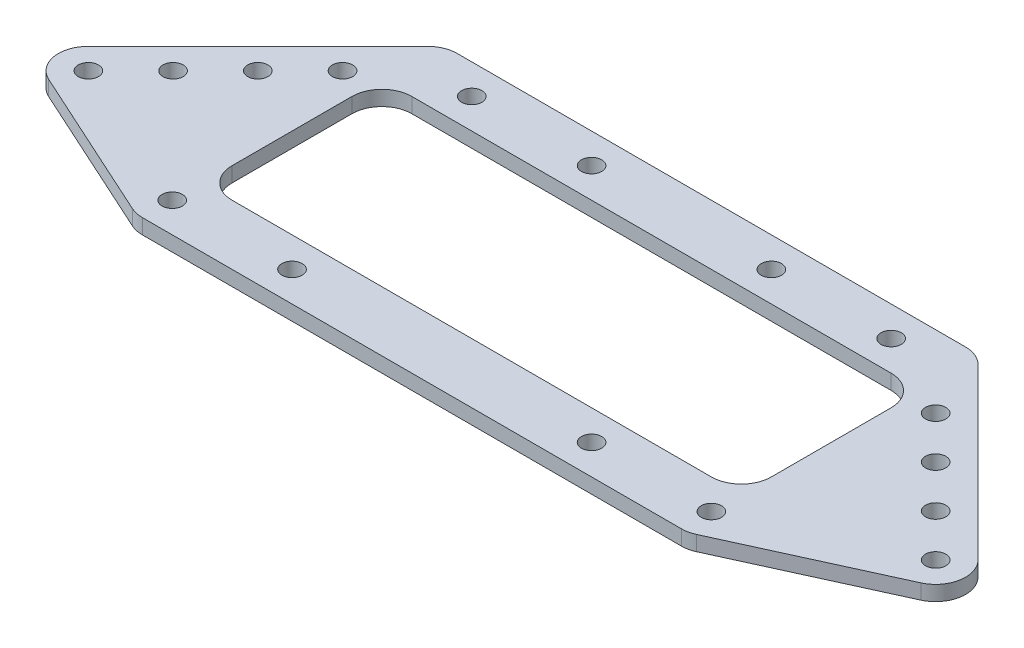
SolidWorks part; units mm, degrees
ref_plane "Front Plane" through (0, 0, 0) normal (0, 0, 1) x (1, 0, 0)
ref_plane "Top Plane" through (0, 0, 0) normal (0, 1, 0) x (1, 0, 0)
ref_plane "Right Plane" through (0, 0, 0) normal (1, 0, 0) x (0, 0, -1)
sketch "Sketch1" plane through (0, 0, 0) normal (0, 1, 0) x (1, 0, 0)
  line L0 (44.45, 0) -> (44.45, -7.0248) construction
  line L1 (98.3315, 6.35) -> (-9.4315, 6.35)
  line L2 (95.25, -6.35) -> (-6.35, -6.35)
  line L3 (-12.7, -12.7) -> (-12.7, -38.1)
  line L4 (-6.35, -44.45) -> (95.25, -44.45)
  line L5 (0, 0) -> (-37.4363, 0) construction
  line L6 (-9.4315, 0) -> (-60.1279, -50.6964) construction
  line L7 (-49.8427, -31.4309) -> (-13.9217, 4.4901)
  line L8 (-47.9856, -41.6994) -> (-15.3331, -56.5784)
  line L9 (-12.7, -57.15) -> (101.6, -57.15)
  line L10 (101.6, -12.7) -> (101.6, -38.1)
  line L11 (136.8856, -41.6994) -> (104.2331, -56.5784)
  line L12 (138.7427, -31.4309) -> (102.8217, 4.4901)
  line L13 (110.5803, -12.2487) -> (44.45, 53.8815) construction
  circle A0 centre (0, 0) radius 2.15
  circle A1 centre (25.4, 0) radius 2.15
  circle A2 centre (-18.4118, -8.9803) radius 2.15
  circle A3 centre (-27.392, -17.9605) radius 2.15
  circle A4 centre (-36.3723, -26.9408) radius 2.15
  circle A5 centre (-45.3526, -35.921) radius 2.15
  arc A7 (-9.4315, 6.35) -> (-13.9217, 4.4901) centre (-9.4315, 0) ccw
  arc A8 (-49.8427, -31.4309) -> (-47.9856, -41.6994) centre (-45.3526, -35.921) ccw
  circle A9 centre (-12.7, -50.8) radius 2.15
  arc A10 (-15.3331, -56.5784) -> (-12.7, -57.15) centre (-12.7, -50.8) ccw
  circle A11 centre (12.7, -50.8) radius 2.15
  arc A12 (-6.35, -44.45) -> (-12.7, -38.1) centre (-6.35, -38.1) cw
  arc A13 (-12.7, -12.7) -> (-6.35, -6.35) centre (-6.35, -12.7) cw
  arc A14 (95.25, -44.45) -> (101.6, -38.1) centre (95.25, -38.1) ccw
  arc A15 (101.6, -12.7) -> (95.25, -6.35) centre (95.25, -12.7) ccw
  circle A16 centre (63.5, 0) radius 2.15
  circle A17 centre (88.9, 0) radius 2.15
  circle A18 centre (107.3118, -8.9803) radius 2.15
  circle A19 centre (116.292, -17.9605) radius 2.15
  circle A20 centre (134.2526, -35.921) radius 2.15
  circle A21 centre (125.2723, -26.9408) radius 2.15
  circle A22 centre (76.2, -50.8) radius 2.15
  circle A23 centre (101.6, -50.8) radius 2.15
  arc A24 (104.2331, -56.5784) -> (101.6, -57.15) centre (101.6, -50.8) cw
  arc A25 (138.7427, -31.4309) -> (136.8856, -41.6994) centre (134.2526, -35.921) cw
  arc A26 (98.3315, 6.35) -> (102.8217, 4.4901) centre (98.3315, 0) cw
  point P16 (-9.4315, 0)
  point P40 (-12.7, -44.45)
  point P43 (-12.7, -6.35)
  point P47 (44.45, -44.45)
  point P50 (44.45, -6.35)
  point P68 (44.45, -57.15)
  point P73 (44.45, 6.35)
  dimension "D1" = 4.3
  dimension "D2" = 4.3
  dimension "D12" = 4.3
  dimension "D17" = 4.3
  dimension "D20" = 4.3
  dimension "D22" = 6.35
  dimension "D10" = 6.35
  dimension "D3" = 25.4
  dimension "D4" = 19.05
  dimension "D5" = 76.2
  dimension "D6" = 6.35
  dimension "D7" = 6.35
  dimension "D8" = 38.1
  dimension "D9" = 57.15
  dimension "D11" = 45
  dimension "D13" = 12.7
  dimension "D15" = 12.7
  dimension "D16" = 6.35
  dimension "D18" = 6.35
  dimension "D19" = 6.35
  dimension "D21" = 25.4
  dimension "D23" = 90
  dimension "D24" = 31.75
  dimension "D14" = 4
extrude "Boss-Extrude1" add sketch "Sketch1" along normal blind 3.175
